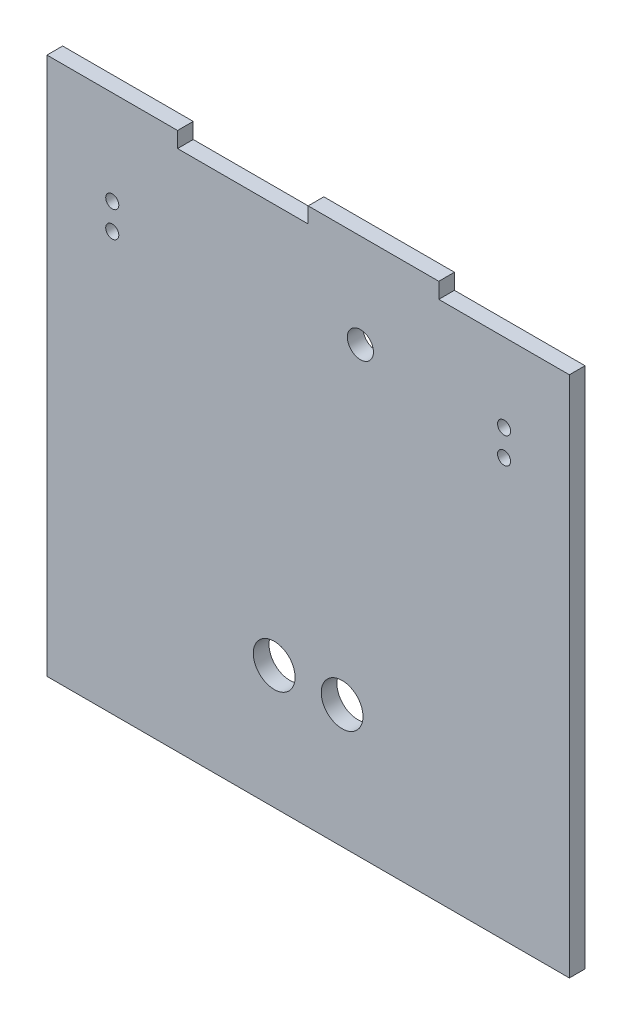
SolidWorks part; units mm, degrees
material "Perspex (TM) Plaque acrylique coulée"
ref_plane "Plan de face" through (0, 0, 0) normal (0, 0, 1) x (1, 0, 0)
ref_plane "Plan de dessus" through (0, 0, 0) normal (0, 1, 0) x (1, 0, 0)
ref_plane "Plan de droite" through (0, 0, 0) normal (1, 0, 0) x (0, 0, -1)
sketch "Esquisse1" plane through (0, 0, 0) normal (0, 0, 1) x (1, 0, 0)
  line L0 (0, 0) -> (200, 0)
  line L1 (200, 0) -> (200, 200)
  line L2 (200, 200) -> (150, 200)
  line L3 (150, 200) -> (150, 206)
  line L4 (150, 206) -> (100, 206)
  line L5 (100, 206) -> (100, 200)
  line L6 (100, 200) -> (50, 200)
  line L7 (50, 200) -> (50, 206)
  line L8 (50, 206) -> (0, 206)
  line L9 (0, 206) -> (0, 0)
  circle A0 centre (175, 170) radius 2.5
  circle A1 centre (175, 160) radius 2.5
  circle A2 centre (25, 170) radius 2.5
  circle A3 centre (25, 160) radius 2.5
  circle A4 centre (120, 170) radius 5
  circle A5 centre (87, 47.15) radius 8
  circle A6 centre (113, 47.15) radius 8
  dimension "D9" = 5
  dimension "D10" = 30
  dimension "D11" = 25
  dimension "D13" = 5
  dimension "D15" = 5
  dimension "D16" = 5
  dimension "D21" = 10
  dimension "D25" = 16
  dimension "D26" = 16
  dimension "D1" = 206
  dimension "D2" = 200
  dimension "D3" = 200
  dimension "D4" = 50
  dimension "D5" = 6
  dimension "D6" = 50
  dimension "D7" = 6
  dimension "D8" = 50
  dimension "D12" = 10
  dimension "D14" = 25
  dimension "D17" = 36
  dimension "D18" = 10
  dimension "D19" = 25
  dimension "D20" = 25
  dimension "D22" = 36
  dimension "D23" = 80
  dimension "D24" = 26
  dimension "D27" = 87
extrude "Boss.-Extru.1" add sketch "Esquisse1" along normal blind 6
